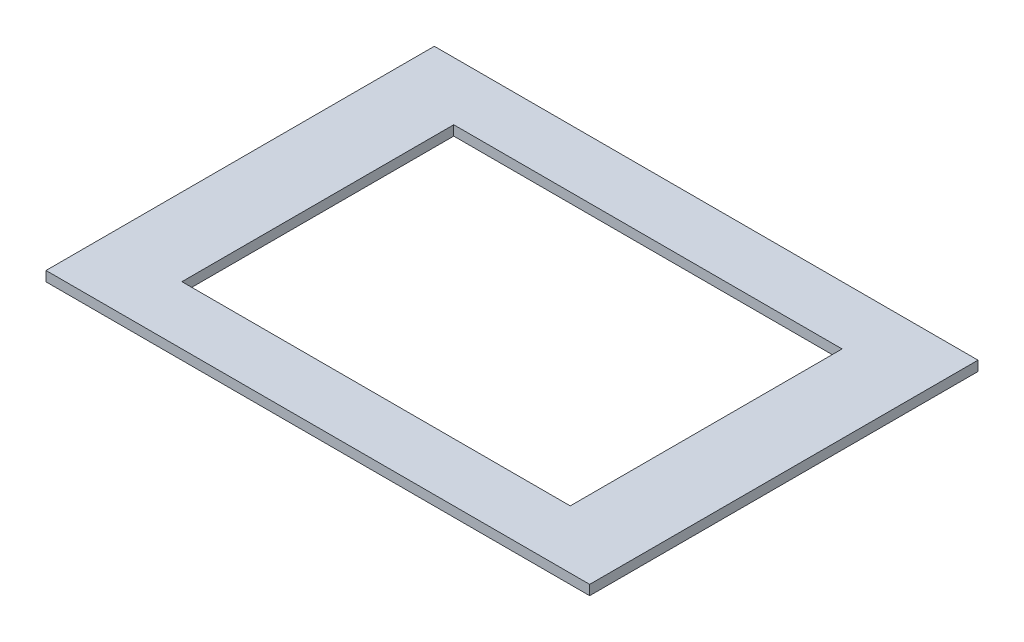
SolidWorks part; units mm, degrees
ref_plane "Front Plane" through (0, 0, 0) normal (0, 0, 1) x (1, 0, 0)
ref_plane "Top Plane" through (0, 0, 0) normal (0, 1, 0) x (1, 0, 0)
ref_plane "Right Plane" through (0, 0, 0) normal (1, 0, 0) x (0, 0, -1)
sketch "Sketch1" plane through (0, 0, 0) normal (0, 1, 0) x (1, 0, 0)
  line L1 (0, 0) -> (700, 0)
  line L2 (0, 0) -> (0, 500)
  line L3 (0, 500) -> (700, 500)
  line L4 (700, 0) -> (700, 500)
  dimension "D1" = 500
  dimension "D2" = 700
extrude "Boss-Extrude1" add sketch "Sketch1" along normal blind 12.7
ref_plane "Plane1" through (0, 0, -250) normal (0, 0, 1) x (1, 0, 0)
ref_plane "Plane2" through (350, 0, 0) normal (1, 0, 0) x (0, 0, -1)
sketch "Sketch2" plane through (0, 12.7, 0) normal (0, 1, 0) x (1, 0, 0)
  line L1 (100, 425) -> (600, 425)
  line L2 (100, 425) -> (100, 75)
  line L3 (100, 75) -> (600, 75)
  line L4 (600, 425) -> (600, 75)
  line L6 (680.95, 75) -> (19.05, 75) construction
  line L7 (680.95, 425) -> (19.05, 425) construction
  line L8 (0, 500) -> (0, 0) construction
  line L9 (700, 0) -> (700, 500) construction
  dimension "D1" = 100
  dimension "D2" = 100
extrude "Cut-Extrude1" cut sketch "Sketch2" against normal through all
